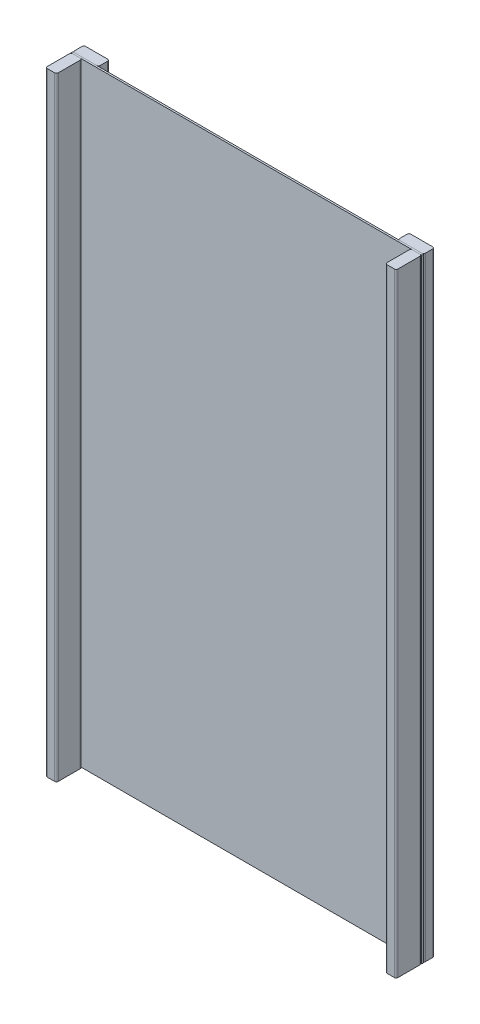
SolidWorks part; units mm, degrees
material "Plywood"
ref_plane "Front Plane" through (0, 0, 0) normal (0, 0, 1) x (1, 0, 0)
ref_plane "Top Plane" through (0, 0, 0) normal (0, 1, 0) x (1, 0, 0)
ref_plane "Right Plane" through (0, 0, 0) normal (1, 0, 0) x (0, 0, -1)
sketch "Sketch1" plane through (0, 0, 0) normal (0, 0, 1) x (1, 0, 0)
  line L1 (-609.6, 0) -> (609.6, 0)
  line L2 (-609.6, 0) -> (-609.6, 2133.6)
  line L3 (-609.6, 2133.6) -> (609.6, 2133.6)
  line L4 (609.6, 0) -> (609.6, 2133.6)
  dimension "D1" = 1219.2
  dimension "D2" = 2133.6
extrude "Boss-Extrude1" add sketch "Sketch1" along normal blind 6.35
sketch "Sketch2" plane through (0, 0, 0) normal (0, 1, 0) x (1, 0, 0)
  line L0 (-609.6, -6.35) -> (609.6, -6.35) construction
  line L1 (603.25, -6.35) -> (577.85, -6.35)
  line L2 (609.6, -12.7) -> (609.6, -88.9)
  line L3 (603.25, -95.25) -> (577.85, -95.25)
  line L4 (571.5, -12.7) -> (571.5, -88.9)
  line L5 (-603.25, -6.35) -> (-577.85, -6.35)
  line L6 (-609.6, -12.7) -> (-609.6, -88.9)
  line L7 (-603.25, -95.25) -> (-577.85, -95.25)
  line L8 (-571.5, -12.7) -> (-571.5, -88.9)
  line L9 (609.6, -6.35) -> (609.6, 0) construction
  line L10 (-609.6, -6.35) -> (-609.6, 0) construction
  arc A0 (-609.6, -88.9) -> (-603.25, -95.25) centre (-603.25, -88.9) ccw
  arc A1 (-577.85, -95.25) -> (-571.5, -88.9) centre (-577.85, -88.9) ccw
  arc A2 (-577.85, -6.35) -> (-571.5, -12.7) centre (-577.85, -12.7) cw
  arc A3 (-603.25, -6.35) -> (-609.6, -12.7) centre (-603.25, -12.7) ccw
  arc A4 (609.6, -88.9) -> (603.25, -95.25) centre (603.25, -88.9) cw
  arc A5 (577.85, -95.25) -> (571.5, -88.9) centre (577.85, -88.9) cw
  arc A6 (577.85, -6.35) -> (571.5, -12.7) centre (577.85, -12.7) ccw
  arc A7 (603.25, -6.35) -> (609.6, -12.7) centre (603.25, -12.7) cw
  point P24 (609.6, -95.25)
  point P27 (571.5, -95.25)
  point P32 (609.6, -6.35)
  dimension "D3" = 6.35
  dimension "D1" = 88.9
  dimension "D2" = 38.1
extrude "Boss-Extrude2" add sketch "Sketch2" along normal up to surface (2133.6 mm away) separate body up to face at (0, 2133.6, 3.175)
sketch "Sketch3" plane through (0, 0, 0) normal (0, 1, 0) x (1, 0, 0)
  line L0 (-609.6, 0) -> (609.6, 0) construction
  line L1 (603.25, 0) -> (527.05, 0)
  line L2 (609.6, 6.35) -> (609.6, 31.75)
  line L3 (603.25, 38.1) -> (527.05, 38.1)
  line L4 (520.7, 6.35) -> (520.7, 31.75)
  line L5 (-603.25, 0) -> (-527.05, 0)
  line L6 (-609.6, 6.35) -> (-609.6, 31.75)
  line L7 (-603.25, 38.1) -> (-527.05, 38.1)
  line L8 (-520.7, 6.35) -> (-520.7, 31.75)
  line L9 (609.6, -6.35) -> (609.6, 0) construction
  line L10 (-609.6, -6.35) -> (-609.6, 0) construction
  arc A0 (-609.6, 31.75) -> (-603.25, 38.1) centre (-603.25, 31.75) cw
  arc A1 (-527.05, 38.1) -> (-520.7, 31.75) centre (-527.05, 31.75) cw
  arc A2 (-527.05, 0) -> (-520.7, 6.35) centre (-527.05, 6.35) ccw
  arc A3 (-603.25, 0) -> (-609.6, 6.35) centre (-603.25, 6.35) cw
  arc A4 (609.6, 31.75) -> (603.25, 38.1) centre (603.25, 31.75) ccw
  arc A5 (527.05, 38.1) -> (520.7, 31.75) centre (527.05, 31.75) ccw
  arc A6 (527.05, 0) -> (520.7, 6.35) centre (527.05, 6.35) cw
  arc A7 (603.25, 0) -> (609.6, 6.35) centre (603.25, 6.35) ccw
  point P24 (609.6, 38.1)
  point P27 (520.7, 38.1)
  point P32 (609.6, 0)
  dimension "D3" = 6.35
  dimension "D1" = 88.9
  dimension "D2" = 38.1
extrude "Boss-Extrude3" add sketch "Sketch3" along normal up to surface (2133.6 mm away) separate body up to face at (0, 2133.6, 3.175)
sketch "Sketch4" [suppressed] plane through (0, 0, 6.35) normal (0, 0, 1) x (1, 0, 0)
  line L0 (0, 261.0236) -> (0, 788.167) construction
  line L1 (-88.9, 1828.8) -> (88.9, 1828.8)
  line L2 (-88.9, 1828.8) -> (-88.9, 1651)
  line L3 (-88.9, 1651) -> (88.9, 1651)
  line L4 (88.9, 1828.8) -> (88.9, 1651)
  point P5 (-88.9, 1739.9)
  dimension "D1" = 177.8
  dimension "D2" = 177.8
  dimension "D3" = 1739.9
extrude "Cut-Extrude1" [suppressed] cut sketch "Sketch4" against normal through all
